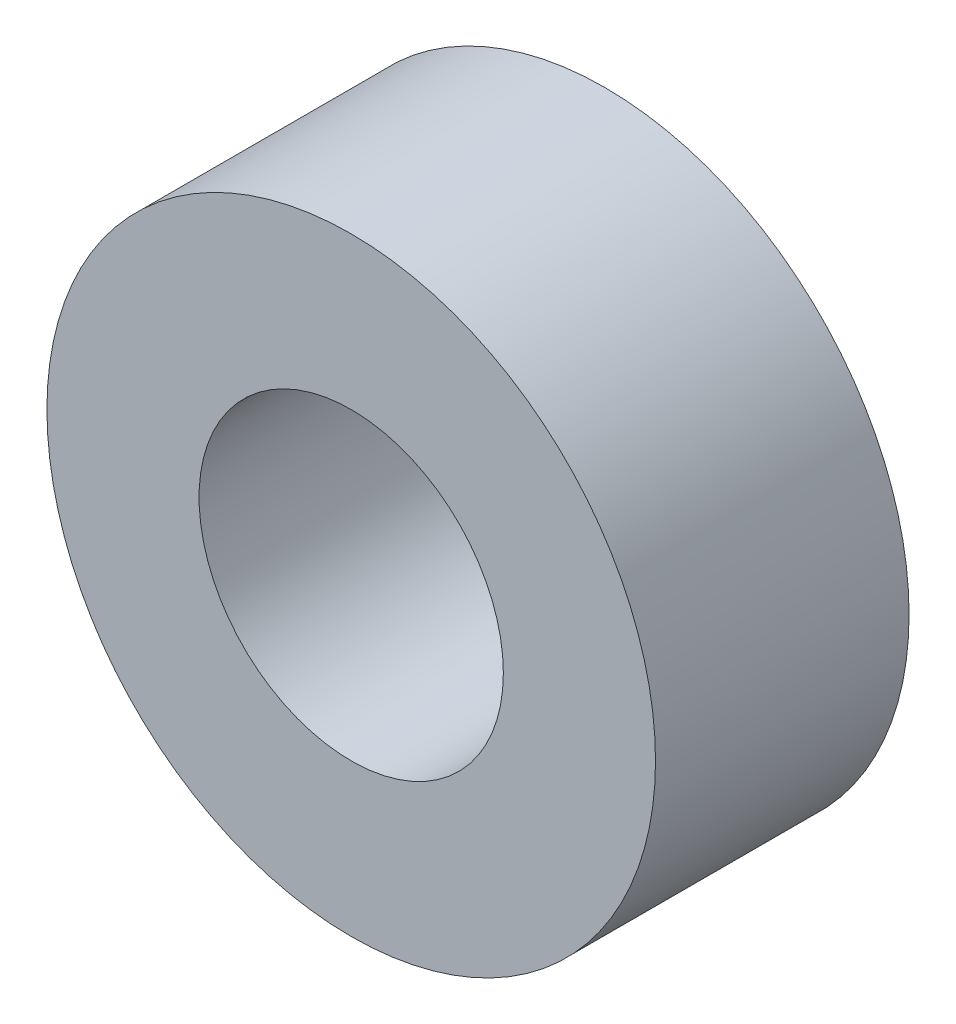
SolidWorks part; units mm, degrees
ref_plane "Front Plane" through (0, 0, 0) normal (0, 0, 1) x (1, 0, 0)
ref_plane "Top Plane" through (0, 0, 0) normal (0, 1, 0) x (1, 0, 0)
ref_plane "Right Plane" through (0, 0, 0) normal (1, 0, 0) x (0, 0, -1)
sketch "Sketch1" plane through (0, 0, 0) normal (0, 0, 1) x (1, 0, 0)
  circle A0 centre (0, 0) radius 3
  circle A1 centre (0, 0) radius 6
  dimension "D1" = 6
  dimension "D2" = 12
extrude "Boss-Extrude1" add sketch "Sketch1" along normal blind 5
